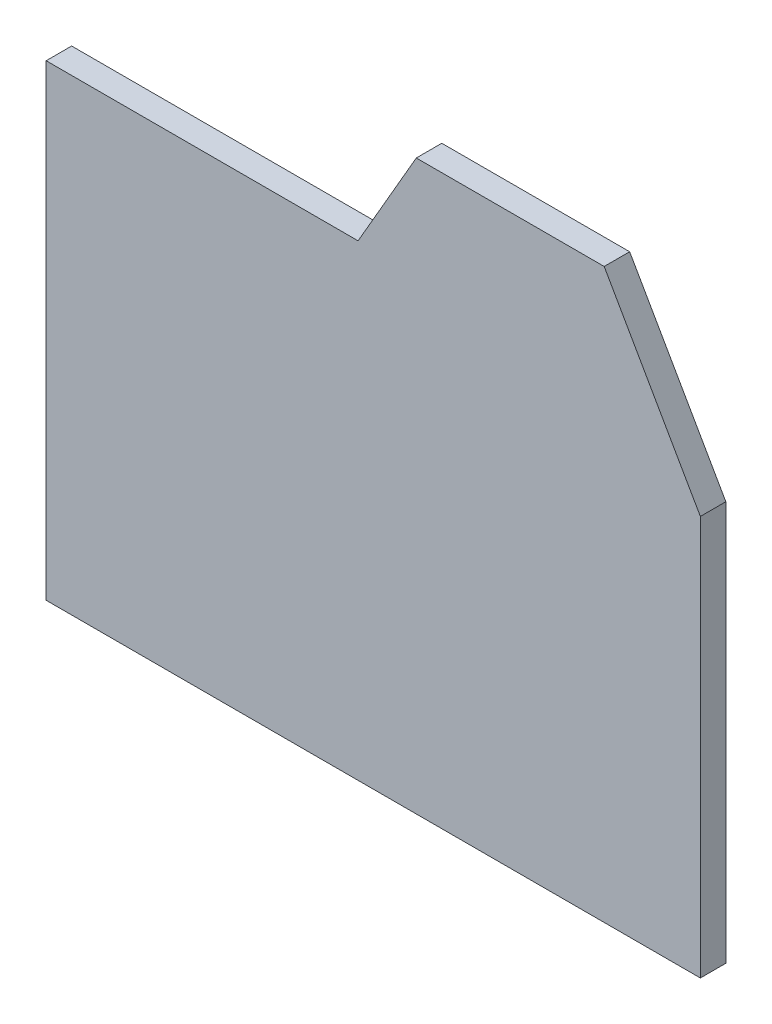
SolidWorks part; units mm, degrees
ref_plane "Front Plane" through (0, 0, 0) normal (0, 0, 1) x (1, 0, 0)
ref_plane "Top Plane" through (0, 0, 0) normal (0, 1, 0) x (1, 0, 0)
ref_plane "Right Plane" through (0, 0, 0) normal (1, 0, 0) x (0, 0, -1)
sketch "Sketch2" plane through (0, 0, 0) normal (0, 0, 1) x (1, 0, 0)
  line L0 (72.2895, 55) -> (72.4094, 55)
  line L1 (0, 0) -> (77, 0)
  line L2 (0, 0) -> (0, 55)
  line L11 (77, 0) -> (77, 47.0489)
  line L12 (0, 55) -> (36.7133, 55)
  line L15 (36.7133, 55) -> (43.5662, 66.8694)
  line L16 (43.5662, 66.8694) -> (65.6794, 66.8694)
  line L17 (65.6794, 66.8694) -> (77, 47.0489)
  dimension "D1" = 77
  dimension "D2" = 55
  dimension "D3" = 36.7133
  dimension "D4" = 47.0489
  dimension "D7" = 22.1133
extrude "Boss-Extrude1" add sketch "Sketch2" along normal blind 3
